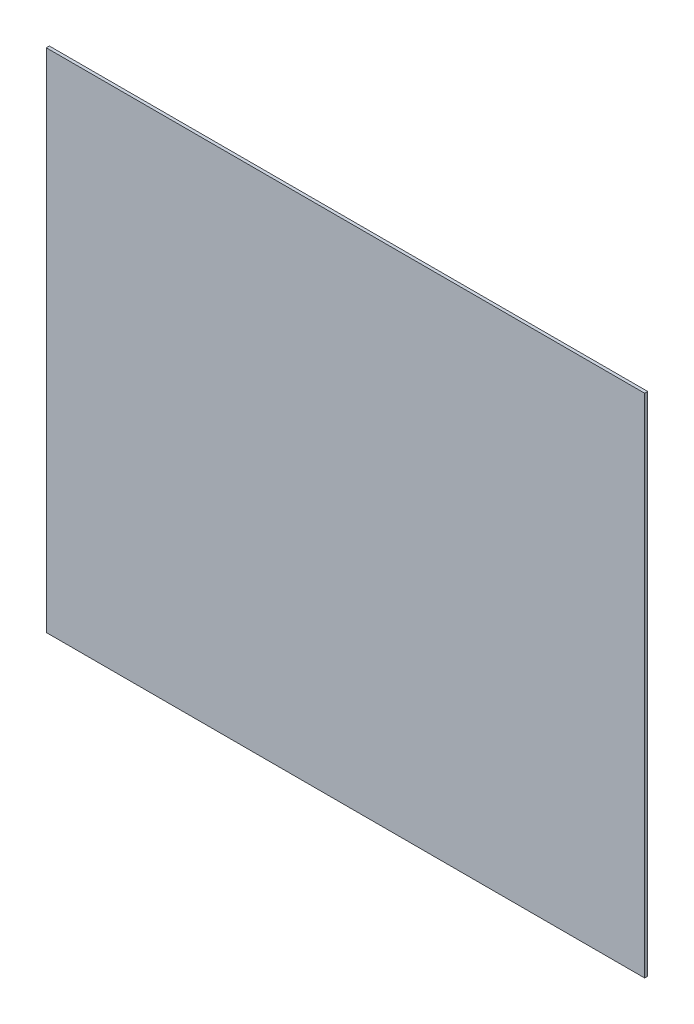
SolidWorks part; units mm, degrees
ref_plane "Front Plane" through (0, 0, 0) normal (0, 0, 1) x (1, 0, 0)
ref_plane "Top Plane" through (0, 0, 0) normal (0, 1, 0) x (1, 0, 0)
ref_plane "Right Plane" through (0, 0, 0) normal (1, 0, 0) x (0, 0, -1)
sketch "Sketch1" plane through (0, 0, 0) normal (0, 0, 1) x (1, 0, 0)
  line L0 (434.96, -507.18) -> (434.96, -501.48) construction
  line L1 (-13.18, 13.18) -> (438.14, 13.18)
  line L2 (-13.18, 13.18) -> (-13.18, -511.36)
  line L3 (-13.18, -511.36) -> (438.14, -511.36)
  line L4 (438.14, 13.18) -> (438.14, -511.36) construction
  line L5 (415.96, -508.18) -> (421.66, -508.18) construction
  line L6 (-10, -507.18) -> (-10, -501.48) construction
  line L7 (415.96, 10) -> (421.66, 10) construction
  line L8 (438.14, -511.36) -> (606.5262, -511.36)
  line L9 (606.5262, -511.36) -> (606.5262, 13.18)
  line L10 (606.5262, 13.18) -> (438.14, 13.18)
  dimension "D1" = 3.18
  dimension "D2" = 3.18
  dimension "D3" = 3.18
  dimension "D4" = 3.18
extrude "Boss-Extrude1" add sketch "Sketch1" along normal blind 3.18 contours L1 L10 L9 L8 L3 L2
